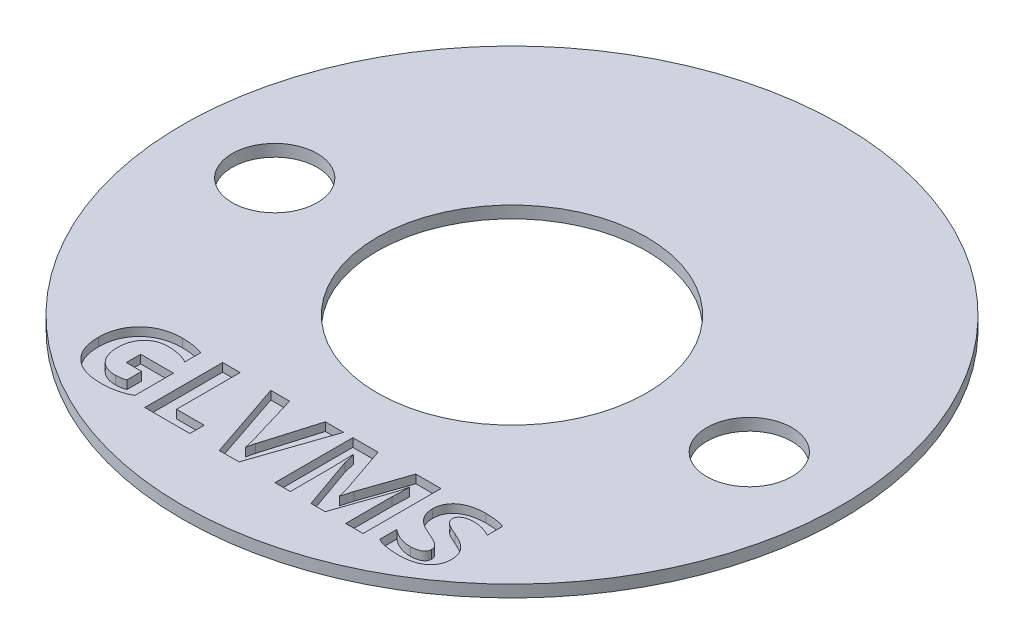
SolidWorks part; units mm, degrees
material "ABS"
ref_plane "Front Plane" through (0, 0, 0) normal (0, 0, 1) x (1, 0, 0)
ref_plane "Top Plane" through (0, 0, 0) normal (0, 1, 0) x (1, 0, 0)
ref_plane "Right Plane" through (0, 0, 0) normal (1, 0, 0) x (0, 0, -1)
sketch "Sketch1" plane through (0, 0, 0) normal (0, 1, 0) x (1, 0, 0)
  circle A0 centre (0, 0) radius 27.5
  dimension "D1" = 55
extrude "Boss-Extrude1" add sketch "Sketch1" along normal blind 1
sketch "Sketch4" plane through (0, 0, 0) normal (0, -1, 0) x (1, 0, 0)
  line L0 (-19.8, 0) -> (19.8, 0) construction
  circle A4 centre (-19.8, 0) radius 3.55
  circle A5 centre (0, 0) radius 11.25
  circle A6 centre (19.8, 0) radius 3.55
  point P1 (19.6621, -7.9829)
  point P2 (0, 0)
  dimension "D1" = 39.6
  dimension "D2" = 22.5
  dimension "D3" = 7.1
extrude "Cut-Extrude2" cut sketch "Sketch4" against normal through all
sketch "Sketch2" plane through (0, 1, 0) normal (0, 1, 0) x (1, 0, 0)
  line L0 (-16, -22) -> (16, -22) construction
  line L1 (0, 0) -> (0, -22) construction
  text T0 "GLVMS" font "Nirmala UI" height 6.5
  dimension "D1" = 32
  dimension "D2" = 22
extrude "Cut-Extrude1" cut sketch "Sketch2" against normal offset from surface (0.7 mm away) 0.3 up to face at (-19.8, 0, -3.55)
